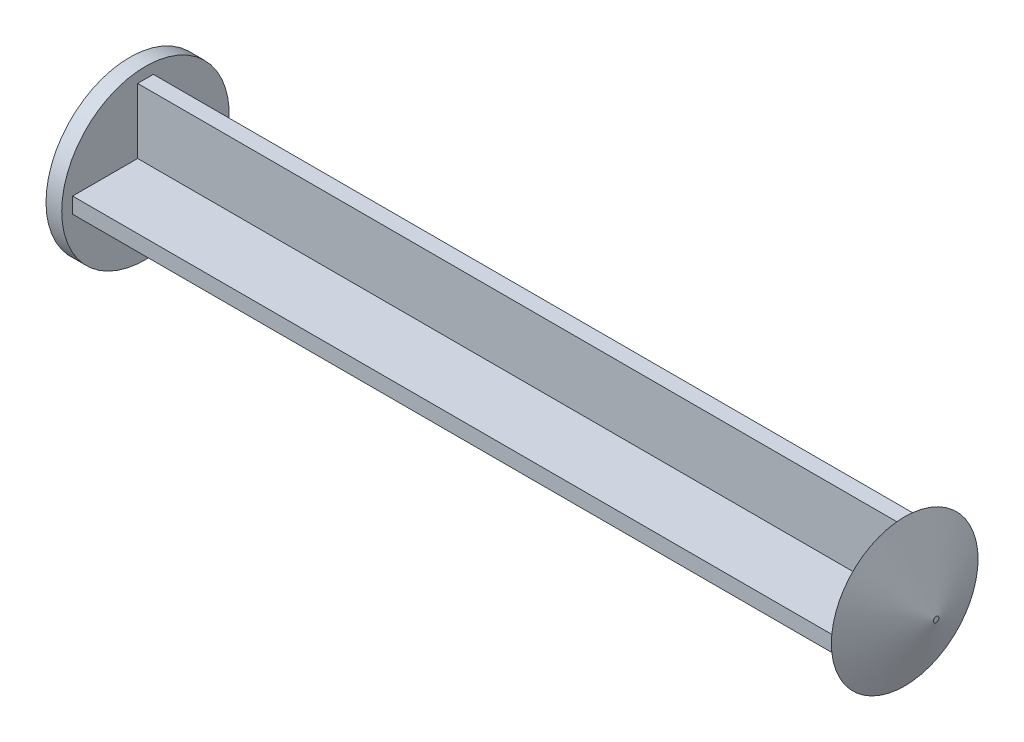
SolidWorks part; units mm, degrees
ref_plane "Front Plane" through (0, 0, 0) normal (0, 0, 1) x (1, 0, 0)
ref_plane "Top Plane" through (0, 0, 0) normal (0, 1, 0) x (1, 0, 0)
ref_plane "Right Plane" through (0, 0, 0) normal (1, 0, 0) x (0, 0, -1)
sketch "Sketch1" plane through (0, 0, 0) normal (1, 0, 0) x (0, 0, -1)
  circle A0 centre (0, 0) radius 14
  dimension "D1" = 28
extrude "Boss-Extrude1" add sketch "Sketch1" along normal blind 6 draft 66
sketch "Sketch2" plane through (0, 0, 0) normal (-1, 0, 0) x (0, 0, 1)
  line L0 (1.5, -1.5) -> (1.5, -13.9194)
  line L1 (-13.9194, -1.5) -> (-1.5, -1.5)
  line L2 (-13.9194, -1.5) -> (-13.9194, 1.5)
  line L3 (-13.9194, 1.5) -> (-1.5, 1.5)
  line L4 (13.9194, -1.5) -> (13.9194, 1.5)
  line L5 (-1.5, -1.5) -> (-1.5, -13.9194)
  line L6 (1.5, -1.5) -> (13.9194, -1.5)
  line L7 (1.5, 13.9194) -> (-1.5, 13.9194)
  line L8 (1.5, 13.9194) -> (1.5, 1.5)
  line L9 (1.5, -13.9194) -> (-1.5, -13.9194)
  line L10 (-1.5, 13.9194) -> (-1.5, 1.5)
  line L11 (1.5, 1.5) -> (13.9194, 1.5)
  circle A0 centre (0, 0) radius 14 construction
  point P0 (0, 0)
  point P8 (0, 0)
  dimension "D1" = 3
  dimension "D2" = 3
extrude "Boss-Extrude2" add sketch "Sketch2" along normal blind 145
sketch "Sketch3" plane through (-145, 0, 0) normal (-1, 0, 0) x (0, 0, 1)
  circle A0 centre (0, 0) radius 16
extrude "Boss-Extrude3" add sketch "Sketch3" along normal blind 3
